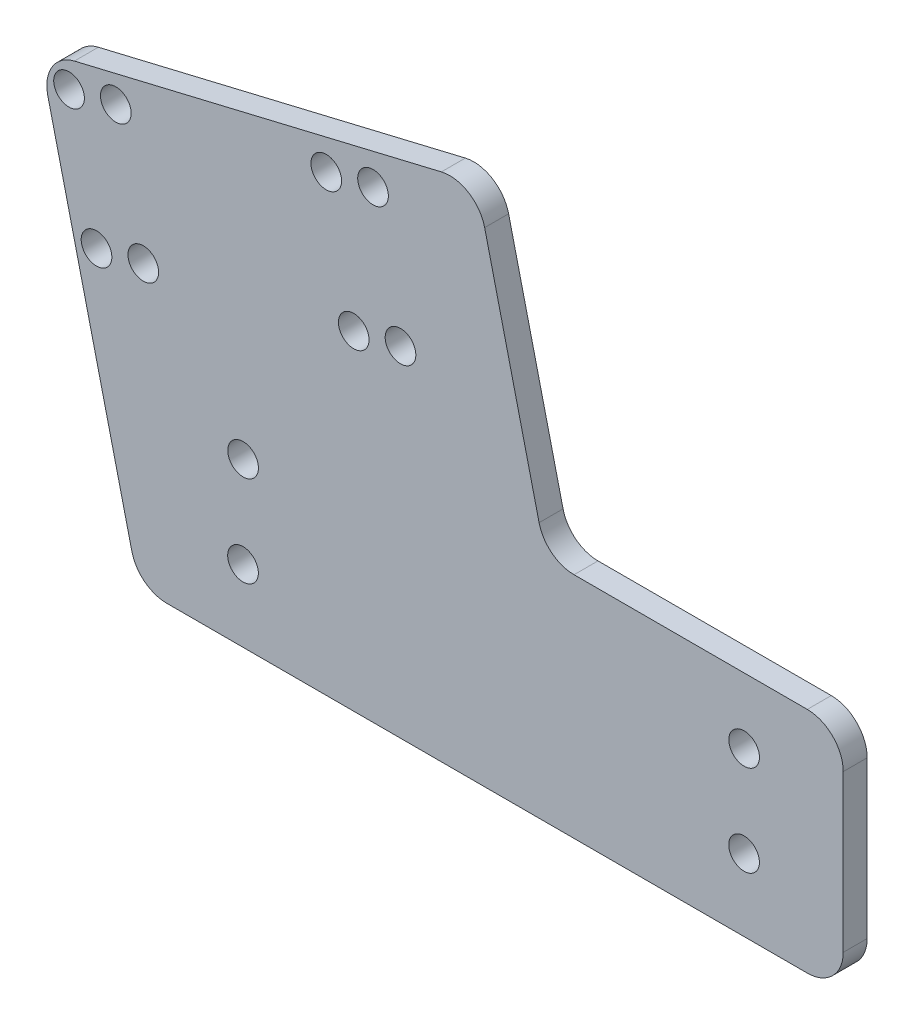
SolidWorks part; units mm, degrees
ref_plane "Front Plane" through (0, 0, 0) normal (0, 0, 1) x (1, 0, 0)
ref_plane "Top Plane" through (0, 0, 0) normal (0, 1, 0) x (1, 0, 0)
ref_plane "Right Plane" through (0, 0, 0) normal (1, 0, 0) x (0, 0, -1)
sketch "Sketch1" plane through (0, 0, 0) normal (0, 0, 1) x (1, 0, 0)
  line L5 (-40.5305, 38.5635) -> (17.3806, 52.3715)
  line L6 (17.3806, 52.3715) -> (26.5742, 13.8136)
  line L7 (26.5742, 13.8136) -> (66.0177, 13.8136)
  line L8 (66.0177, 13.8136) -> (66.0177, -16.4623)
  line L9 (66.0177, -16.4623) -> (-27.4104, -16.4623)
  line L10 (-27.4104, -16.4623) -> (-40.5305, 38.5635)
  circle A0 centre (-36.6096, 36.0526) radius 2.032
  circle A1 centre (-30.4101, 37.427) radius 2.032
  circle A2 centre (-32.9675, 19.624) radius 2.032
  circle A3 centre (52.8751, -6.9291) radius 2.032 construction
  circle A4 centre (-13.5459, -6.9291) radius 2.032 construction
  arc A5 (9.0124, 27.4193) -> (8.3736, 30.3006) centre (7.3291, 28.5576) ccw construction
  arc A6 (8.3736, 30.3006) -> (9.0124, 27.4193) centre (7.3291, 28.5576) ccw construction
  arc A7 (5.3703, 43.8479) -> (4.7315, 46.7292) centre (3.687, 44.9862) ccw construction
  arc A8 (4.7315, 46.7292) -> (5.3703, 43.8479) centre (3.687, 44.9862) ccw construction
  arc A9 (-3.557, 41.8688) -> (-4.1957, 44.7501) centre (-2.5125, 43.6118) ccw construction
  arc A10 (-4.1957, 44.7501) -> (-3.557, 41.8688) centre (-2.5125, 43.6118) ccw construction
  arc A11 (0.0852, 25.4402) -> (-0.5536, 28.3214) centre (1.1297, 27.1832) ccw construction
  arc A12 (-0.5536, 28.3214) -> (0.0852, 25.4402) centre (1.1297, 27.1832) ccw construction
  arc A13 (-25.0847, 19.8602) -> (-25.7235, 22.7414) centre (-26.768, 20.9984) ccw construction
  arc A14 (-25.7235, 22.7414) -> (-25.0847, 19.8602) centre (-26.768, 20.9984) ccw construction
  circle A15 centre (52.8751, -6.9291) radius 2.032
  circle A16 centre (-13.5459, -6.9291) radius 2.032
  arc A17 (9.0124, 27.4193) -> (8.3736, 30.3006) centre (7.3291, 28.5576) ccw
  arc A18 (8.3736, 30.3006) -> (9.0124, 27.4193) centre (7.3291, 28.5576) ccw
  arc A19 (5.3703, 43.8479) -> (4.7315, 46.7292) centre (3.687, 44.9862) ccw
  arc A20 (4.7315, 46.7292) -> (5.3703, 43.8479) centre (3.687, 44.9862) ccw
  arc A21 (-3.557, 41.8688) -> (-4.1957, 44.7501) centre (-2.5125, 43.6118) ccw
  arc A22 (-4.1957, 44.7501) -> (-3.557, 41.8688) centre (-2.5125, 43.6118) ccw
  arc A23 (0.0852, 25.4402) -> (-0.5536, 28.3214) centre (1.1297, 27.1832) ccw
  arc A24 (-0.5536, 28.3214) -> (0.0852, 25.4402) centre (1.1297, 27.1832) ccw
  arc A25 (-25.0847, 19.8602) -> (-25.7235, 22.7414) centre (-26.768, 20.9984) ccw
  arc A26 (-25.7235, 22.7414) -> (-25.0847, 19.8602) centre (-26.768, 20.9984) ccw
  ellipse E0 centre (52.8831, 5.1359) end of major axis (52.8831, 3.1039) minor radius 2.032 construction
  ellipse E1 centre (-13.5379, 5.1359) end of major axis (-13.5379, 7.1679) minor radius 2.032 construction
  ellipse E2 centre (52.8831, 5.1359) end of major axis (52.8831, 7.1679) minor radius 2.032
  ellipse E3 centre (-13.5379, 5.1359) end of major axis (-13.5379, 7.1679) minor radius 2.032
extrude "Boss-Extrude1" add sketch "Sketch1" along normal blind 3.175
fillet "Fillet1" radius 4.7625 6 edges at (-27.4104, -16.4623, 1.5875) (66.0177, -16.4623, 1.5875) (66.0177, 13.8136, 1.5875) (26.5742, 13.8136, 1.5875) (17.3806, 52.3715, 1.5875) (-40.5305, 38.5635, 1.5875)
